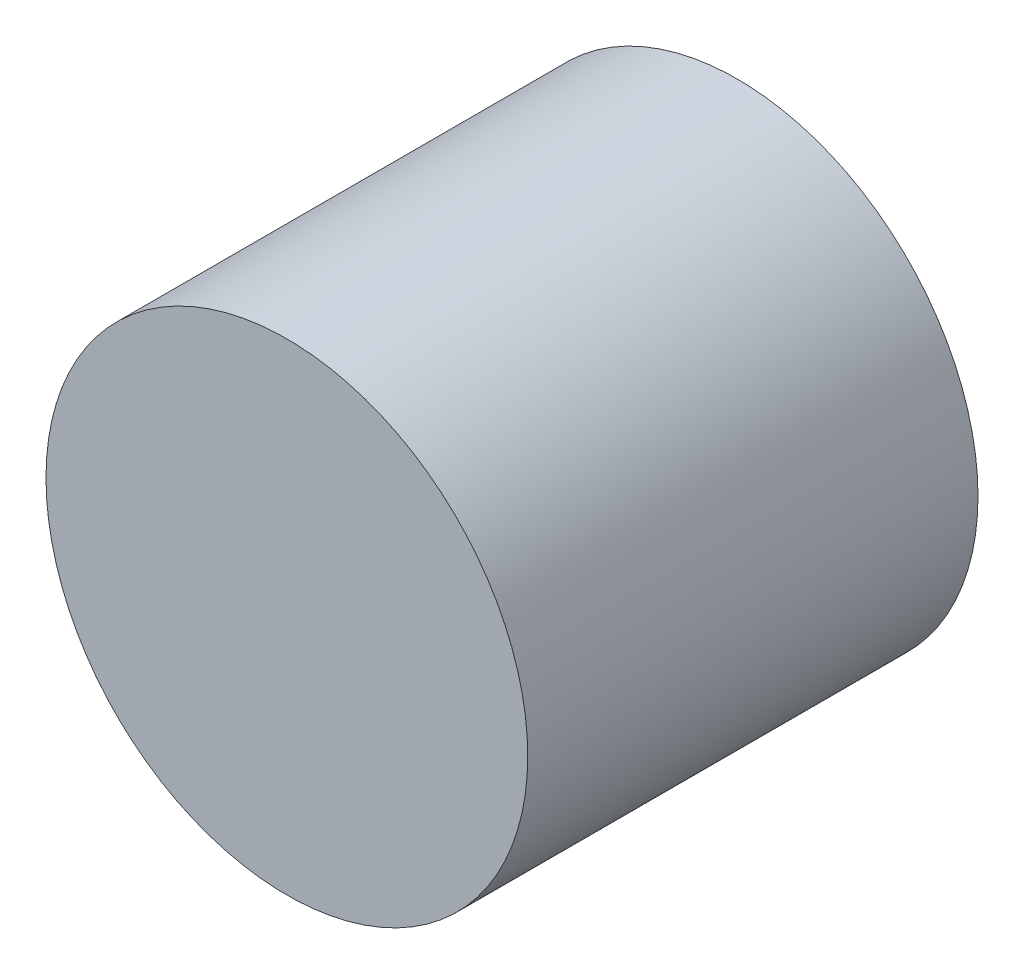
SolidWorks part; units mm, degrees
ref_plane "Front Plane" through (0, 0, 0) normal (0, 0, 1) x (1, 0, 0)
ref_plane "Top Plane" through (0, 0, 0) normal (0, 1, 0) x (1, 0, 0)
ref_plane "Right Plane" through (0, 0, 0) normal (1, 0, 0) x (0, 0, -1)
sketch "Sketch1" plane through (0, 0, 0) normal (0, 0, 1) x (1, 0, 0)
  circle A0 centre (0, 0) radius 95.123
  dimension "D1" = 190.246
extrude "Boss-Extrude1" add sketch "Sketch1" along normal blind 177.8
